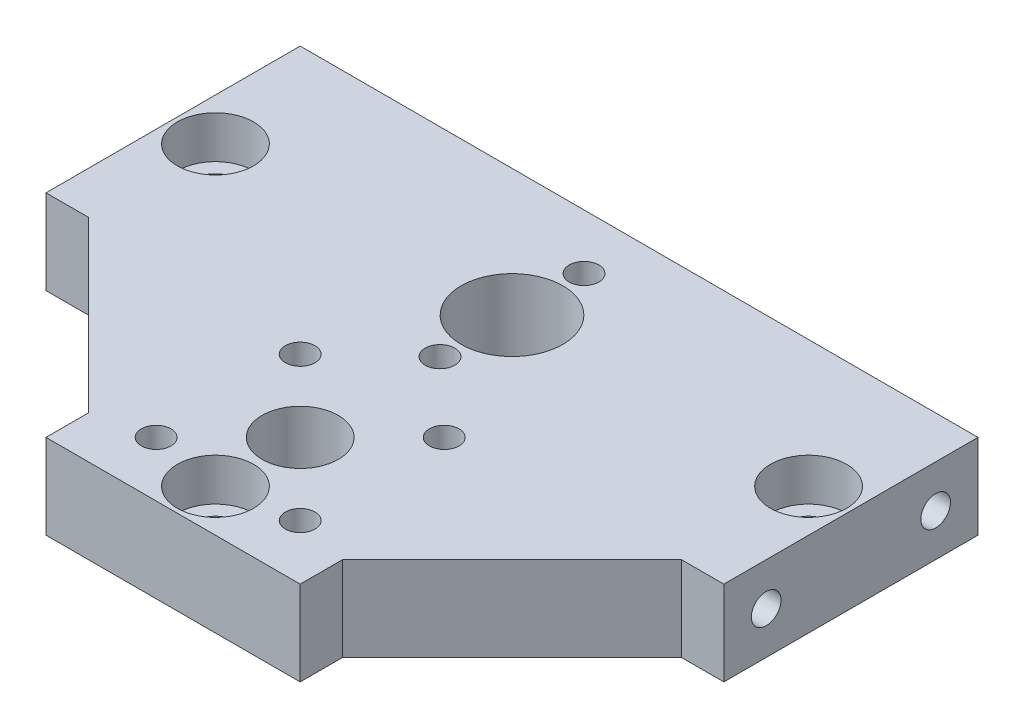
SolidWorks part; units mm, degrees
ref_plane "Front Plane" through (0, 0, 0) normal (0, 0, 1) x (1, 0, 0)
ref_plane "Top Plane" through (0, 0, 0) normal (0, 1, 0) x (1, 0, 0)
ref_plane "Right Plane" through (0, 0, 0) normal (1, 0, 0) x (0, 0, -1)
sketch "Sketch1" plane through (0, 0, 0) normal (0, 1, 0) x (1, 0, 0)
  line L1 (-40, 15) -> (40, 15)
  line L2 (-40, 15) -> (-40, -15)
  line L3 (-40, -15) -> (40, -15)
  line L4 (40, 15) -> (40, -15)
  line L5 (-40, 15) -> (40, -15) construction
  line L6 (-40, -15) -> (40, 15) construction
  circle A0 centre (0, 0) radius 8.5 construction
  circle A1 centre (0, 8.5) radius 1.75
  circle A2 centre (0, -8.5) radius 1.75
  circle A3 centre (0, 0) radius 6
  circle A4 centre (-35, 0) radius 2.75
  circle A5 centre (35, 0) radius 2.75
  point P0 (0, 0)
  point P18 (40, 0)
  dimension "D1" = 17
  dimension "D4" = 3.5
  dimension "D6" = 12
  dimension "D7" = 5
  dimension "D8" = 5.5
  dimension "D2" = 70
  dimension "D3" = 30
  dimension "D9" = 5
  dimension "D5" = 2
extrude "Boss-Extrude1" add sketch "Sketch1" along normal blind 10
sketch "Sketch4" plane through (0, 0, 0) normal (1, 0, 0) x (0, 0, -1)
  line L0 (-15, 10) -> (-40, 10)
  line L1 (-40, 10) -> (-40, 0)
  line L5 (-40, 0) -> (-15, 0)
  line L7 (-15, 0) -> (-15, 10)
  dimension "D3" = 40
extrude "Boss-Extrude3" add sketch "Sketch4" along normal mid plane 30
sketch "Sketch5" plane through (0, 10, 0) normal (0, 1, 0) x (1, 0, 0)
  line L0 (15, -40) -> (-15, -40) construction
  circle A0 centre (0, -35) radius 2.75
  dimension "D1" = 5
  dimension "D2" = 5.5
extrude "Cut-Extrude1" cut sketch "Sketch5" against normal blind 30
chamfer "Chamfer2" distance 20 angle 45 2 edges at (15, 5, 15) (-15, 5, 15)
sketch "Sketch6" plane through (0, 10, 0) normal (0, 1, 0) x (1, 0, 0)
  line L0 (15, -40) -> (-15, -40) construction
  line L1 (8.5, -33.5) -> (-8.5, -33.5) construction
  line L2 (8.5, -33.5) -> (8.5, -16.5) construction
  line L3 (8.5, -16.5) -> (-8.5, -16.5) construction
  line L4 (-8.5, -33.5) -> (-8.5, -16.5) construction
  line L5 (8.5, -33.5) -> (-8.5, -16.5) construction
  line L6 (8.5, -16.5) -> (-8.5, -33.5) construction
  circle A0 centre (-8.5, -16.5) radius 1.75
  circle A1 centre (8.5, -16.5) radius 1.75
  circle A2 centre (8.5, -33.5) radius 1.75
  circle A3 centre (-8.5, -33.5) radius 1.75
  circle A4 centre (0, -25) radius 4.5
  point P0 (0, -25)
  point P12 (0, -25)
  dimension "D3" = 3.5
  dimension "D2" = 9
  dimension "D1" = 17
  dimension "15" = 15
extrude "Cut-Extrude2" cut sketch "Sketch6" against normal blind 30
sketch "Sketch8" plane through (40, 0, 0) normal (1, 0, 0) x (0, 0, -1)
  line L0 (-15, 10) -> (15, 10) construction
  line L1 (-15, 10) -> (-15, 0) construction
  circle A0 centre (-10, 5) radius 1.75
  circle A1 centre (10, 5) radius 1.75
  dimension "D1" = 5
  dimension "D2" = 3.5
  dimension "D3" = 20
  dimension "D4" = 5
extrude "Cut-Extrude3" cut sketch "Sketch8" against normal through all
sketch "Sketch12" plane through (0, 0, 0) normal (0, -1, 0) x (1, 0, 0)
  circle A0 centre (0, 35) radius 4.5
  circle A1 centre (35, 0) radius 4.5
  circle A2 centre (-35, 0) radius 4.5
  dimension "D3" = 9
extrude "Cut-Extrude13" cut sketch "Sketch12" against normal through all from offset 5 offset against normal yes
chamfer "Chamfer3" distance 1 angle 45 4 edges at (8.5, 0, 35.25) (-8.5, 0, 35.25) (-8.5, 0, 18.25) (8.5, 0, 18.25)
